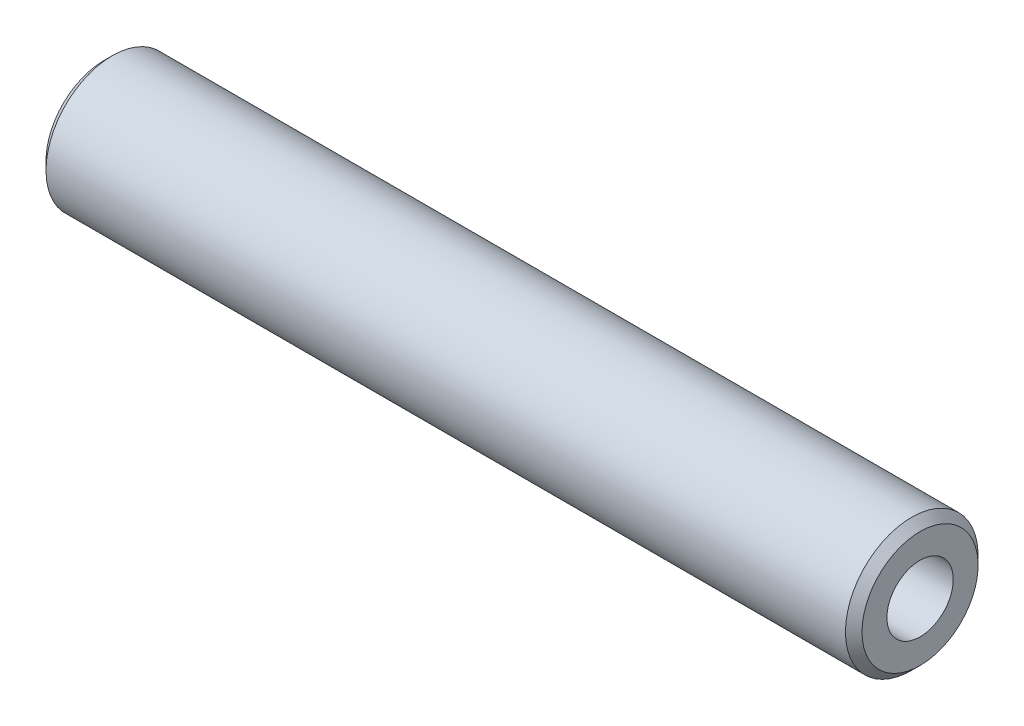
SolidWorks part; units mm, degrees
material "1.4301 (X5CrNi18-10)"
ref_plane "正面" through (0, 0, 0) normal (0, 0, 1) x (1, 0, 0)
ref_plane "平面" through (0, 0, 0) normal (0, 1, 0) x (1, 0, 0)
ref_plane "右側面" through (0, 0, 0) normal (1, 0, 0) x (0, 0, -1)
sketch "ｽｹｯﾁ1" plane through (0, 0, 0) normal (0, 0, 1) x (1, 0, 0)
  line L0 (0, 0) -> (21203.2319, 0) construction
  line L2 (-24.6, 0) -> (24.6, 0)
  line L3 (-24.6, 0) -> (-24.6, 4)
  line L4 (-24.6, 4) -> (24.6, 4)
  line L5 (24.6, 0) -> (24.6, 4)
  point P7 (0, 0)
  dimension "D1" = 8
  dimension "D2" = 49.2
revolve "回転1" add sketch "ｽｹｯﾁ1" angle 360 about L0
hole_wizard "M4x0.7 ねじ穴1" positions "3Dｽｹｯﾁ1" profile "ｽｹｯﾁ3" tap size "M4x0.7" standard "JIS"
sketch3d "3Dｽｹｯﾁ1"
  line L0 (24.6, 0, 0) -> (-24.6, 0, 0) construction
  point P0 (24.6, 0, 0)
  point P4 (-24.6, 0, 0)
sketch "ｽｹｯﾁ3" plane through (24.6, 0, 0) normal (0, 1, 0) x (0, 0, -1)
  line L0 (0, 0) -> (0, 12.4914)
  line L1 (0, 12.4914) -> (1.65, 11.5)
  line L2 (1.65, 11.5) -> (1.65, 8)
  line L3 (1.65, 8) -> (2, 8)
  line L4 (2, 8) -> (2, 0)
  line L5 (2, 0) -> (0, 0)
  line L10 (0, 12.4914) -> (-1.65, 11.5) construction
  line L11 (0, -6.35) -> (0, 107.95) construction
  dimension "ねじ下穴ﾄﾞﾘﾙ直径" = 3.3
  dimension "ねじ下穴ﾄﾞﾘﾙの深さ" = 11.5
  dimension "ねじ山の主要直径" = 4
  dimension "ねじ山の深さ" = 8
  dimension "ﾄﾞﾘﾙ角度" = 118
chamfer "面取り1" distance 0.5 angle 45 2 edges at (-24.6, 0, 4) (24.6, 0, 4)
